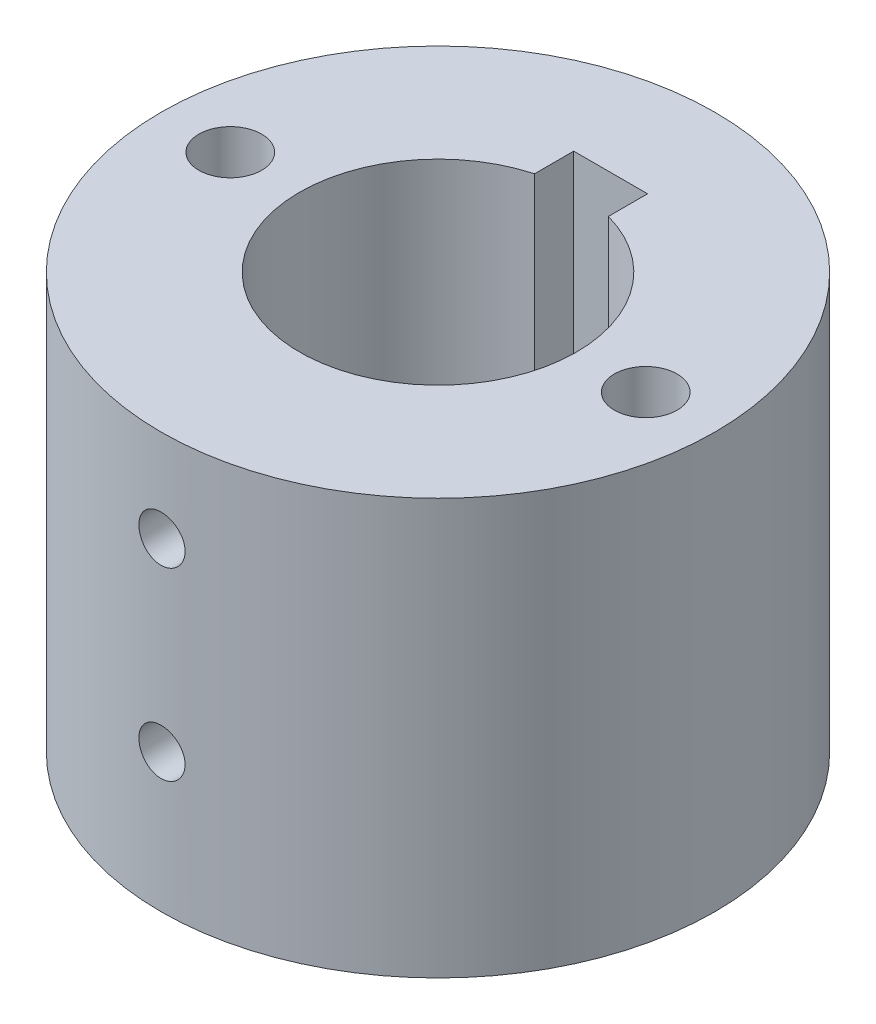
SolidWorks part; units mm, degrees
material "6061-T6 (SS)"
ref_plane "Front Plane" through (0, 0, 0) normal (0, 0, 1) x (1, 0, 0)
ref_plane "Top Plane" through (0, 0, 0) normal (0, 1, 0) x (1, 0, 0)
ref_plane "Right Plane" through (0, 0, 0) normal (1, 0, 0) x (0, 0, -1)
sketch "Sketch2" plane through (0, 0, 0) normal (0, 1, 0) x (1, 0, 0)
  circle A0 centre (0, 0) radius 15
  circle A2 centre (0, 0) radius 30
  dimension "D1" = 30
  dimension "D2" = 60
extrude "Boss-Extrude1" add sketch "Sketch2" along normal blind 45
sketch "Sketch5" plane through (0, 45, 0) normal (0, 1, 0) x (1, 0, 0)
  circle A0 centre (0, 0) radius 22.5 construction
  circle A1 centre (0, 0) radius 15 construction
  circle A2 centre (22.5, 0) radius 3.4
  circle A3 centre (-22.5, 0) radius 3.4
  dimension "D1" = 7.5
  dimension "D2" = 6.8
extrude "Cut-Extrude2" cut sketch "Sketch5" against normal blind 15
ref_plane "Plane1" through (0, 0, 30) normal (0, 0, 1) x (1, 0, 0)
sketch "Sketch7" plane through (0, 0, 30) normal (0, 0, 1) x (1, 0, 0)
  line L0 (0, 0) -> (0, 45) construction
  line L1 (15, 45) -> (-15, 45) construction
  circle A0 centre (0, 35) radius 2.5
  circle A1 centre (0, 15) radius 2.5
  dimension "D1" = 15
  dimension "D2" = 5
  dimension "D3" = 20
extrude "Cut-Extrude3" cut sketch "Sketch7" against normal blind 23
sketch "Sketch8" plane through (0, 45, 0) normal (0, 1, 0) x (1, 0, 0)
  line L0 (0, 15) -> (0, 18.7) construction
  line L1 (-4, 18.7) -> (4, 18.7)
  line L2 (-4, 18.7) -> (-4, 12.7)
  line L3 (4, 18.7) -> (4, 12.7)
  line L4 (4, 12.7) -> (-4, 12.7)
  circle A0 centre (0, 0) radius 15 construction
  point P9 (0, 18.7)
  dimension "D1" = 3.7
  dimension "D2" = 8
  dimension "D3" = 6
extrude "Cut-Extrude4" cut sketch "Sketch8" against normal through all
